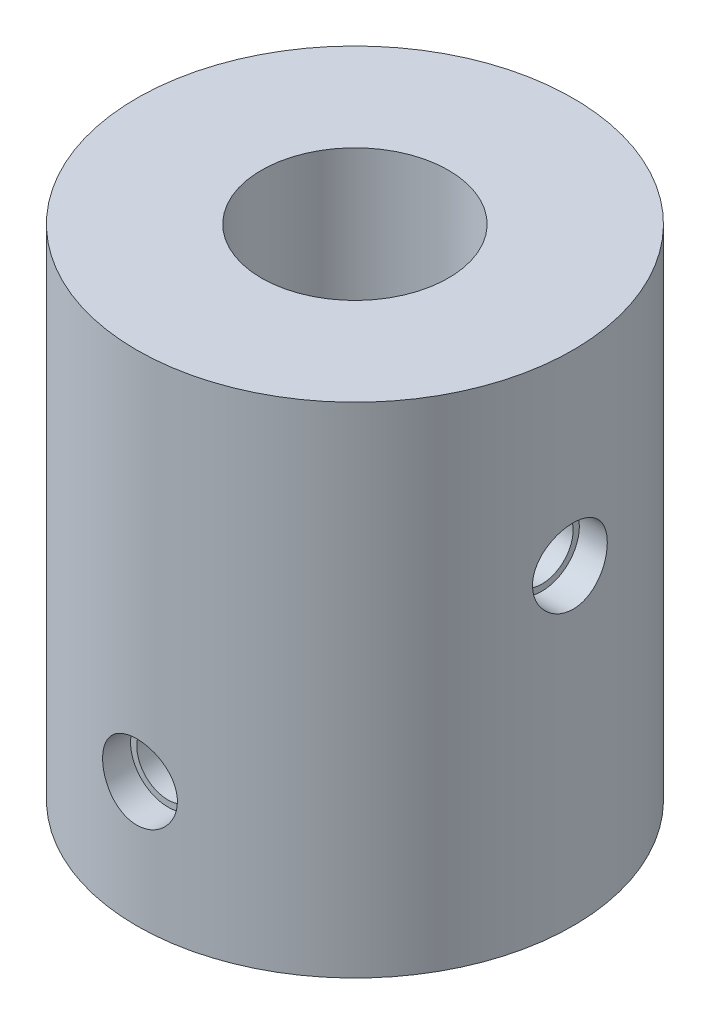
SolidWorks part; units mm, degrees
ref_plane "Front Plane" through (0, 0, 0) normal (0, 0, 1) x (1, 0, 0)
ref_plane "Top Plane" through (0, 0, 0) normal (0, 1, 0) x (1, 0, 0)
ref_plane "Right Plane" through (0, 0, 0) normal (1, 0, 0) x (0, 0, -1)
sketch "Sketch1" plane through (0, 0, 0) normal (0, 1, 0) x (1, 0, 0)
  circle A0 centre (0, 0) radius 1.5
  circle A1 centre (0, 0) radius 3.5
  dimension "D1" = 7
  dimension "D2" = 3
extrude "Boss-Extrude1" add sketch "Sketch1" along normal blind 8
sketch "Sketch2" plane through (0, 0, 0) normal (1, 0, 0) x (0, 0, -1)
  circle A0 centre (0, 5) radius 0.5
  point P4 (0.7309, 12)
  point P5 (2.1166, 12)
  point P6 (0, 0)
  dimension "D2" = 1
  dimension "D1" = 5
extrude "Cut-Extrude1" cut sketch "Sketch2" against normal up to next and the other way up to next
sketch "Sketch3" plane through (0, 0, 0) normal (0, 0, 1) x (1, 0, 0)
  circle A0 centre (0, 2) radius 0.5
  point P2 (0, 0)
  dimension "D1" = 1
  dimension "D2" = 2
extrude "Cut-Extrude2" cut sketch "Sketch3" against normal mid plane 7
sketch "Sketch4" plane through (0, 0, 0) normal (0, 0, 1) x (1, 0, 0)
  circle A2 centre (0, 2) radius 0.6
  circle A3 centre (0, 2) radius 0.6
  dimension "D1" = 0.1
extrude "Cut-Extrude3" cut sketch "Sketch4" against normal blind 1 from offset 4
sketch "Sketch7" plane through (0, 0, 0) normal (1, 0, 0) x (0, 0, -1)
  circle A2 centre (0, 5) radius 0.6
  circle A3 centre (0, 5) radius 0.6
  dimension "D1" = 0.1
extrude "Cut-Extrude4" cut sketch "Sketch7" against normal blind 1 from offset 4
